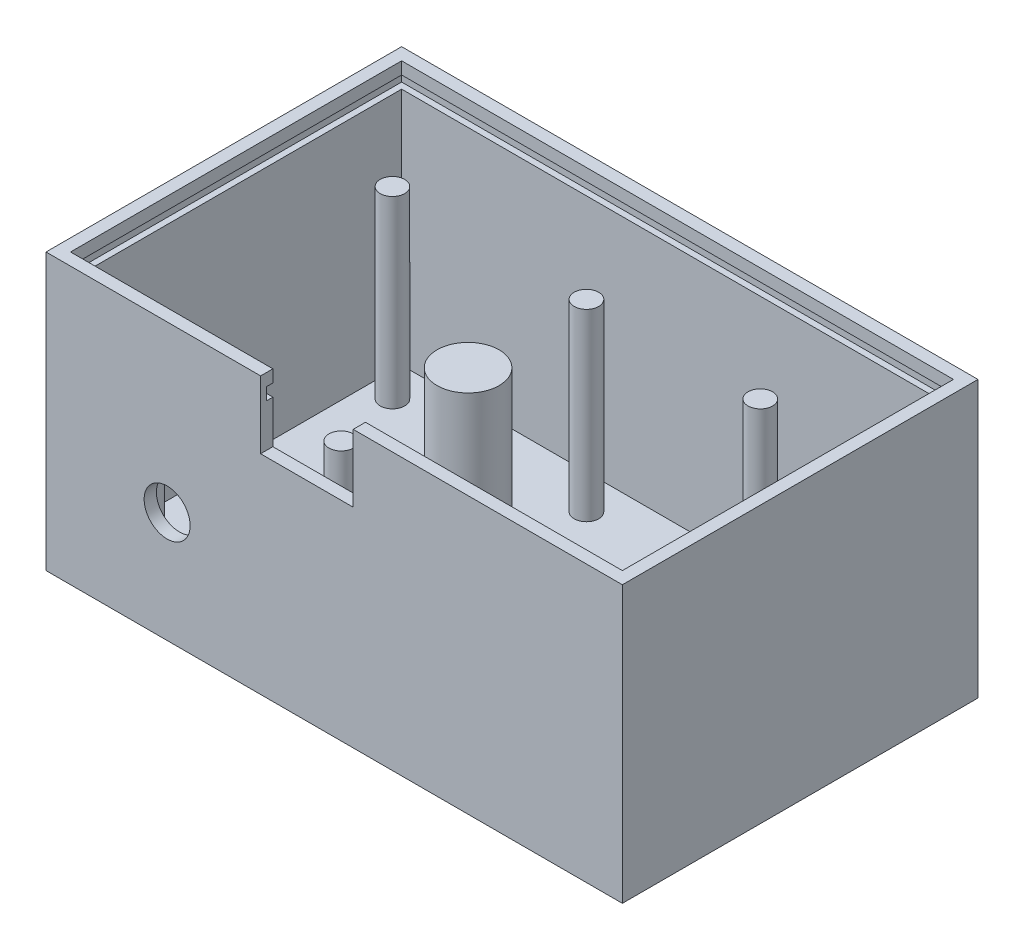
SolidWorks part; units mm, degrees
ref_plane "Front Plane" through (0, 0, 0) normal (0, 0, 1) x (1, 0, 0)
ref_plane "Top Plane" through (0, 0, 0) normal (0, 1, 0) x (1, 0, 0)
ref_plane "Right Plane" through (0, 0, 0) normal (1, 0, 0) x (0, 0, -1)
sketch "Sketch1" plane through (0, 0, 0) normal (0, 1, 0) x (1, 0, 0)
  line L1 (0, 0) -> (94, 0)
  line L2 (0, 0) -> (0, 58)
  line L3 (0, 58) -> (94, 58)
  line L4 (94, 0) -> (94, 58)
  dimension "D1" = 94
  dimension "D2" = 58
extrude "Boss-Extrude1" add sketch "Sketch1" along normal blind 45
sketch "Sketch2" plane through (0, 45, 0) normal (0, 1, 0) x (1, 0, 0)
  line L0 (47, 58) -> (47, 57) construction
  line L1 (0, 58) -> (0, 0) construction
  line L2 (92, 29) -> (94, 29)
  line L3 (47, 2) -> (47, 0)
  line L4 (0, 0) -> (94, 0) construction
  line L5 (94, 58) -> (0, 58) construction
  line L6 (0, 29) -> (0.7071, 28.2929) construction
  line L8 (94, 0) -> (94, 58) construction
  line L10 (2, 56) -> (92, 56)
  line L11 (2, 56) -> (2, 2)
  line L12 (2, 2) -> (92, 2)
  line L13 (92, 56) -> (92, 2)
  dimension "D1" = 2
  dimension "D3" = 1
  dimension "D4" = 1
  dimension "D5" = 90
  dimension "D6" = 54
extrude "Cut-Extrude1" cut sketch "Sketch2" against normal blind 43 contours L13 L12 L11 L10
ref_plane "InsertPlane" through (0, 43, 0) normal (0, -1, 0) x (-1, 0, 0)
sketch "Sketch6" plane through (0, 43, 0) normal (0, -1, 0) x (-1, 0, 0)
  line L0 (-47, 1) -> (-47, 0) construction
  line L1 (-94, 29) -> (-93, 29) construction
  line L2 (-94, 0) -> (-94, 58) construction
  line L3 (0, 0) -> (-94, 0) construction
  line L6 (-93, 57) -> (-1, 57)
  line L7 (-93, 57) -> (-93, 1)
  line L8 (-93, 1) -> (-1, 1)
  line L9 (-1, 57) -> (-1, 1)
  dimension "D1" = 1
  dimension "D2" = 1
  dimension "D3" = 56
  dimension "D4" = 92
extrude "Cut-Extrude2" cut sketch "Sketch6" along normal blind 2
sketch "Sketch10" plane through (0, 2, 0) normal (0, 1, 0) x (1, 0, 0)
  line L0 (6, 50.5) -> (66, 50.5) construction
  line L1 (66, 50.5) -> (66, 10.5) construction
  line L2 (6, 58) -> (6, 50.5) construction
  line L3 (94, 58) -> (0, 58) construction
  line L5 (0, 50.5) -> (6, 50.5) construction
  line L6 (0, 58) -> (0, 0) construction
  circle A0 centre (6, 50.5) radius 2
  circle A1 centre (66, 50.5) radius 2
  circle A2 centre (6, 10.5) radius 2
  circle A3 centre (66, 10.5) radius 2
  circle A4 centre (37.7618, 50.379) radius 2
  circle A5 centre (37.7618, 10.379) radius 2
  circle A6 centre (37.7618, 31.0736) radius 5.0561
  dimension "D1" = 4
  dimension "D2" = 60
  dimension "D3" = 40
  dimension "D4" = 7.5
  dimension "D5" = 6
extrude "Boss-Extrude2" add sketch "Sketch10" along normal blind 30
sketch "Sketch11" plane through (0, 0, 0) normal (0, 0, 1) x (1, 0, 0)
  circle A0 centre (19.7552, 18.0837) radius 3.75
  dimension "D1" = 7.5
extrude "Cut-Extrude3" cut sketch "Sketch11" against normal blind 2
ref_plane "CoverPlane" through (0, 45, 0) normal (0, 1, 0) x (1, 0, 0)
sketch "Sketch12" plane through (0, 45, 0) normal (0, 1, 0) x (1, 0, 0)
  line L0 (0, 2) -> (35, 2) construction
  line L1 (0, 58) -> (0, 0) construction
  line L2 (0, 0) -> (94, 0) construction
  line L3 (35, 2) -> (50.1, 2)
  line L4 (35, 2) -> (35, 0)
  line L5 (35, 0) -> (50.1, 0)
  line L6 (50.1, 2) -> (50.1, 0)
  dimension "D1" = 35
  dimension "D2" = 15.1
  dimension "D3" = 2
extrude "Cut-Extrude4" cut sketch "Sketch12" against normal blind 11
sketch "Sketch13" plane through (0, 2, 0) normal (0, 1, 0) x (1, 0, 0)
sketch "Sketch14" plane through (0, 45, 0) normal (0, 1, 0) x (1, 0, 0)
